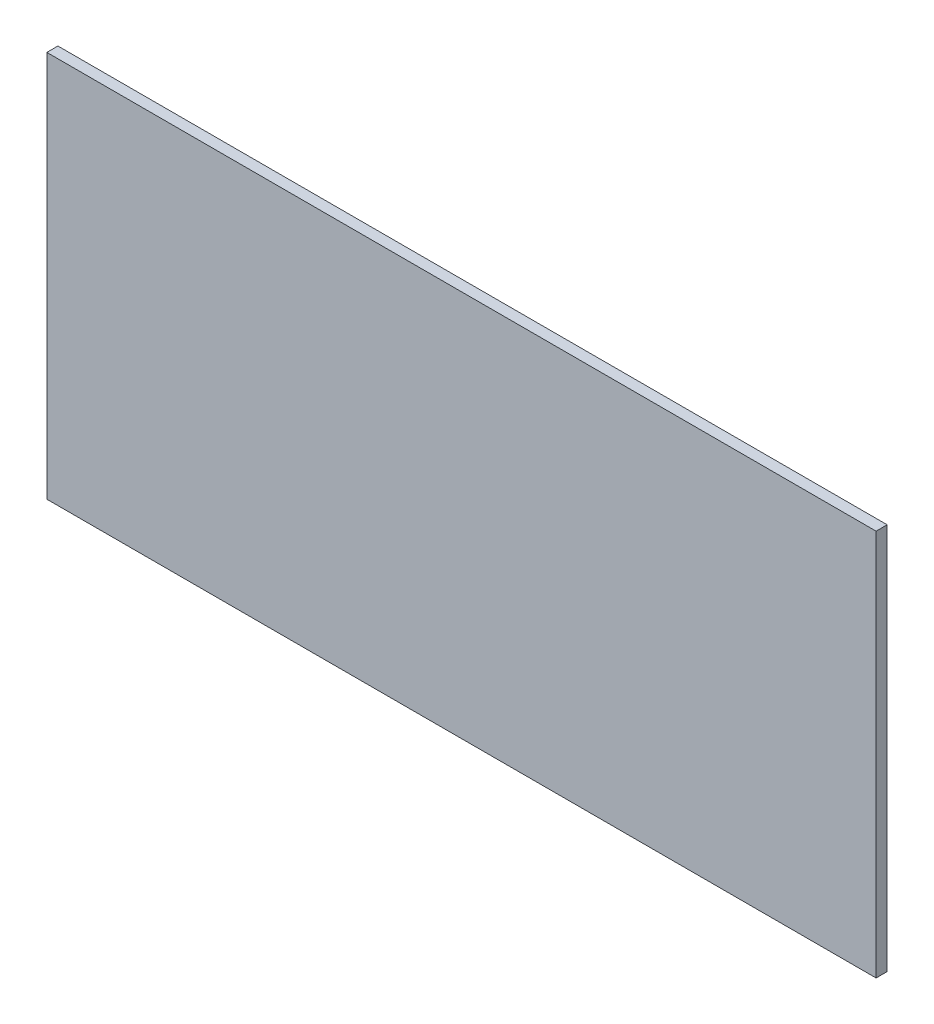
SolidWorks part; units mm, degrees
material "Brass"
ref_plane "Front Plane" through (0, 0, 0) normal (0, 0, 1) x (1, 0, 0)
ref_plane "Top Plane" through (0, 0, 0) normal (0, 1, 0) x (1, 0, 0)
ref_plane "Right Plane" through (0, 0, 0) normal (1, 0, 0) x (0, 0, -1)
sketch "Sketch1" plane through (0, 0, 0) normal (0, 0, 1) x (1, 0, 0)
  line L0 (0, 0) -> (300, 0)
  line L1 (300, 0) -> (300, 140)
  line L2 (300, 140) -> (0, 140)
  line L3 (0, 140) -> (0, 0)
extrude "Boss-Extrude1" add sketch "Sketch1" along normal blind 4
